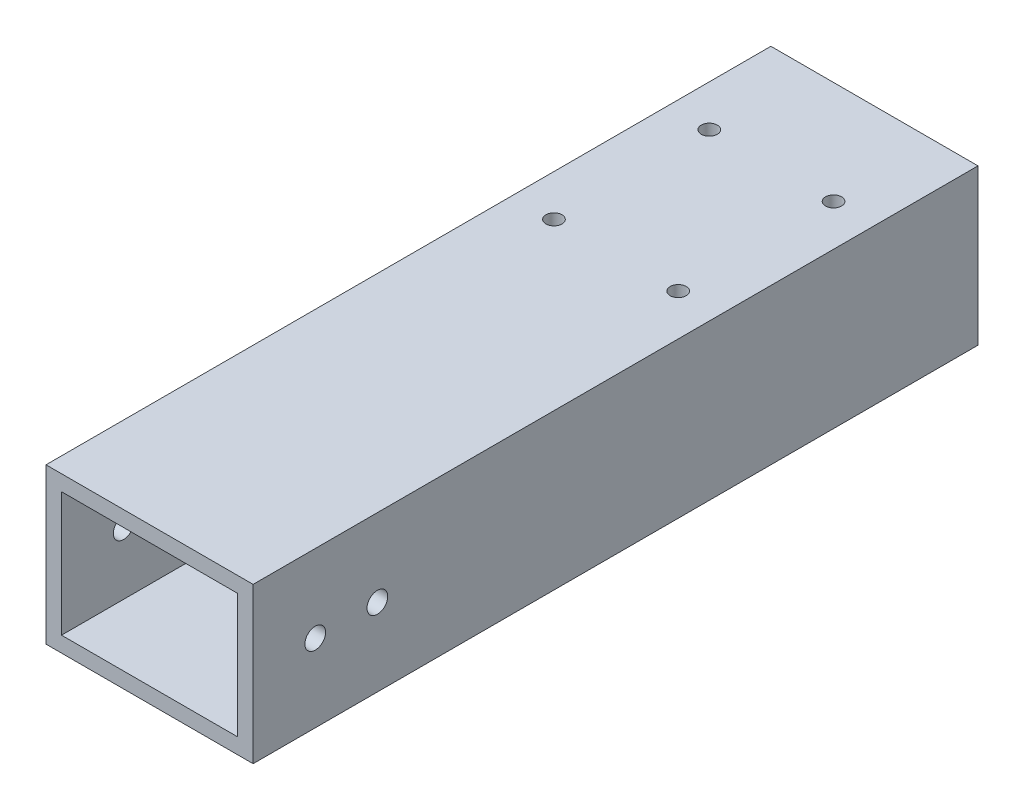
SolidWorks part; units mm, degrees
material "AISI 1015 钢，冷拔 (SS)"
ref_plane "前视基准面" through (0, 0, 0) normal (0, 0, 1) x (1, 0, 0)
ref_plane "上视基准面" through (0, 0, 0) normal (0, 1, 0) x (1, 0, 0)
ref_plane "右视基准面" through (0, 0, 0) normal (1, 0, 0) x (0, 0, -1)
other "Configuration Table"
sketch "草图1" plane through (0, 0, 0) normal (0, 0, 1) x (1, 0, 0)
  line L1 (0, 0) -> (40, 0)
  line L2 (0, 0) -> (0, 30)
  line L3 (0, 30) -> (40, 30)
  line L4 (40, 0) -> (40, 30)
  line L5 (3, 3) -> (37, 3)
  line L6 (3, 3) -> (3, 27)
  line L7 (3, 27) -> (37, 27)
  line L8 (37, 3) -> (37, 27)
  dimension "D1" = 40
  dimension "D2" = 30
  dimension "D3" = 3
  dimension "D4" = 3
  dimension "D5" = 3
  dimension "D6" = 3
extrude "凸台-拉伸1" add sketch "草图1" along normal blind 140
sketch "草图2" plane through (0, 0, 0) normal (1, 0, 0) x (0, 0, -1)
  line L0 (-70, 83.174) -> (-70, -57.7734) construction
  line L1 (-140, 30) -> (0, 30) construction
  line L2 (-234.5233, 15) -> (4.3455, 15) construction
  line L3 (0, 0) -> (0, 30) construction
  line L4 (-140, 0) -> (-140, 30) construction
  circle A0 centre (-116, 15) radius 2
  circle A1 centre (-128, 15) radius 2
  point P2 (-70, 30)
  point P7 (0, 15)
  dimension "D1" = 4
  dimension "D2" = 12
  dimension "D3" = 12
extrude "切除-拉伸1" cut sketch "草图2" along normal through all
sketch "草图3" plane through (0, 0, 0) normal (0, 1, 0) x (1, 0, 0)
  line L0 (20, 7.4176) -> (20, -220.6816) construction
  line L1 (-71.6968, -34.9) -> (105.9098, -34.9) construction
  circle A0 centre (8, -19.9) radius 1.55
  circle A1 centre (32, -19.9) radius 1.55
  circle A2 centre (32, -49.9) radius 1.55
  circle A3 centre (8, -49.9) radius 1.55
  dimension "D1" = 3.1
  dimension "D2" = 20
  dimension "D3" = 24
  dimension "D4" = 19.9
  dimension "D5" = 30
extrude "切除-拉伸2" cut sketch "草图3" along normal through all
